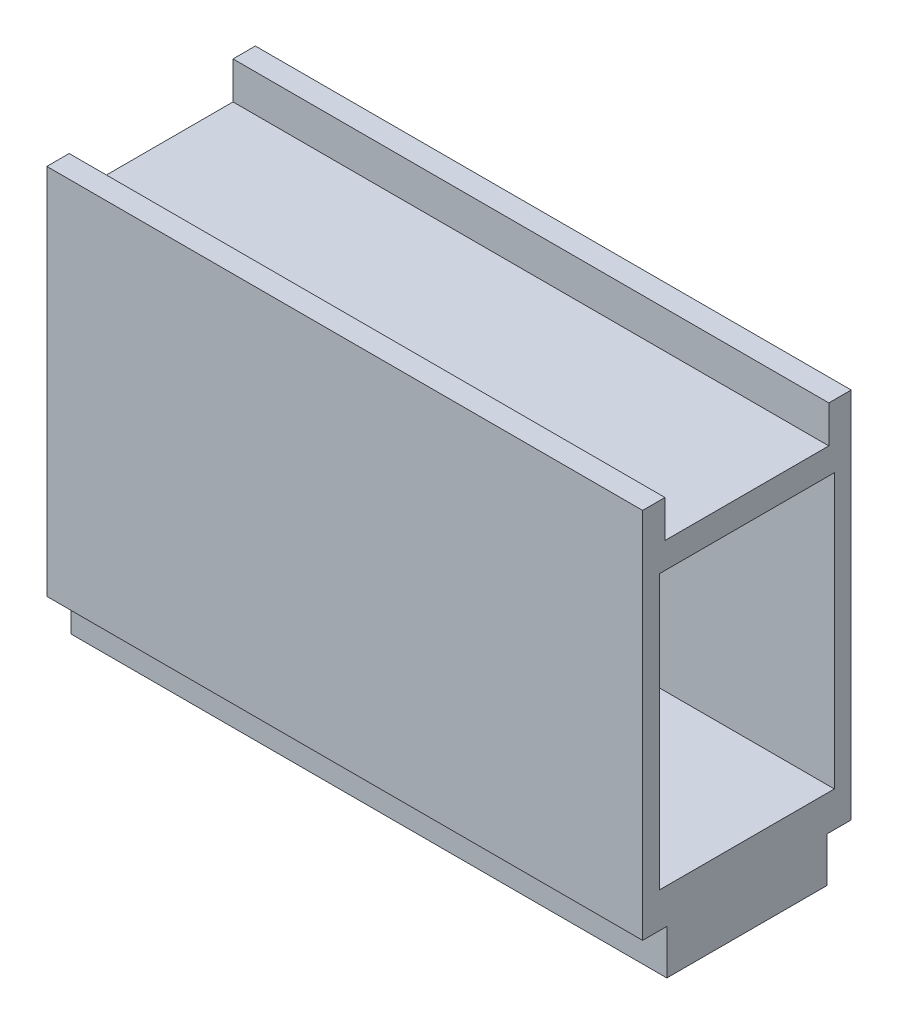
SolidWorks part; units mm, degrees
ref_plane "Front Plane" through (0, 0, 0) normal (0, 0, 1) x (1, 0, 0)
ref_plane "Top Plane" through (0, 0, 0) normal (0, 1, 0) x (1, 0, 0)
ref_plane "Right Plane" through (0, 0, 0) normal (1, 0, 0) x (0, 0, -1)
sketch "Sketch1" plane through (0, 0, 0) normal (0, 1, 0) x (1, 0, 0)
  line L1 (-40, 10.75) -> (40, 10.75)
  line L2 (-40, 10.75) -> (-40, -10.75)
  line L3 (-40, -10.75) -> (40, -10.75)
  line L4 (40, 10.75) -> (40, -10.75)
  line L5 (-40, 10.75) -> (40, -10.75) construction
  line L6 (-40, -10.75) -> (40, 10.75) construction
  point P0 (0, 0)
  dimension "D1" = 21.5
  dimension "D2" = 80
extrude "Boss-Extrude1" add sketch "Sketch1" along normal blind 6
sketch "Sketch2" plane through (0, 6, 0) normal (0, 1, 0) x (1, 0, 0)
  line L1 (-40, 14) -> (40, 14)
  line L2 (-40, 14) -> (-40, -14)
  line L3 (-40, -14) -> (40, -14)
  line L4 (40, 14) -> (40, -14)
  line L5 (-40, 14) -> (40, -14) construction
  line L6 (-40, -14) -> (40, 14) construction
  point P0 (0, 0)
  dimension "D1" = 80
  dimension "D2" = 28
extrude "Boss-Extrude2" add sketch "Sketch2" along normal blind 50
sketch "Sketch3" plane through (0, 56, 0) normal (0, 1, 0) x (1, 0, 0)
  line L0 (40, -14) -> (40, 14) construction
  line L1 (-40, 11) -> (40, 11)
  line L2 (-40, 11) -> (-40, -11)
  line L3 (-40, -11) -> (40, -11)
  line L4 (40, 11) -> (40, -11)
  line L5 (-40, 11) -> (40, -11) construction
  line L6 (-40, -11) -> (40, 11) construction
  point P0 (0, 0)
  dimension "D1" = 22
extrude "Cut-Extrude1" cut sketch "Sketch3" against normal blind 5
sketch "Sketch4" plane through (40, 0, 0) normal (1, 0, 0) x (0, 0, -1)
  line L1 (-11.7434, 47.5128) -> (11.7434, 47.5128)
  line L2 (-11.7434, 47.5128) -> (-11.7434, 10.7375)
  line L3 (-11.7434, 10.7375) -> (11.7434, 10.7375)
  line L4 (11.7434, 47.5128) -> (11.7434, 10.7375)
  line L5 (-11.7434, 47.5128) -> (11.7434, 10.7375) construction
  line L6 (-11.7434, 10.7375) -> (11.7434, 47.5128) construction
  point P0 (0, 29.1251)
  point P1 (0, 29.1251)
extrude "Cut-Extrude2" cut sketch "Sketch4" against normal up to next
